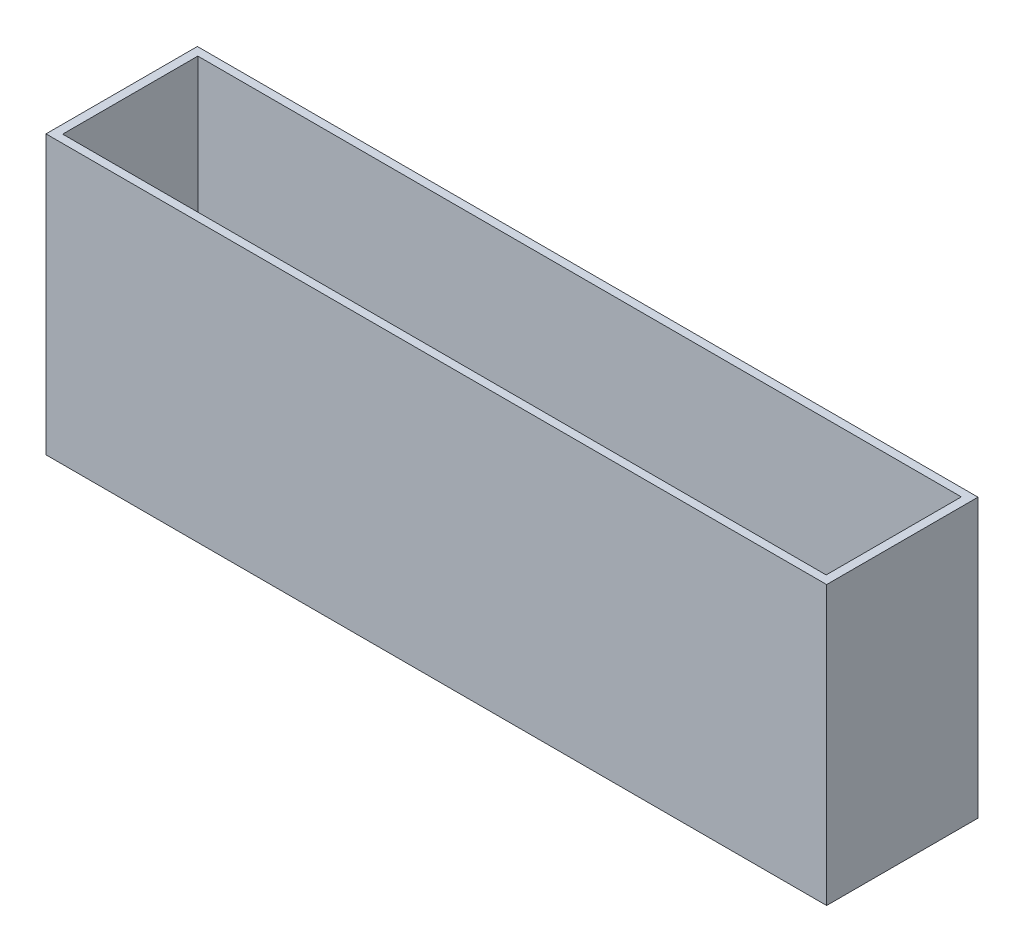
SolidWorks part; units mm, degrees
ref_plane "Front Plane" through (0, 0, 0) normal (0, 0, 1) x (1, 0, 0)
ref_plane "Top Plane" through (0, 0, 0) normal (0, 1, 0) x (1, 0, 0)
ref_plane "Right Plane" through (0, 0, 0) normal (1, 0, 0) x (0, 0, -1)
sketch "Sketch1" plane through (0, 0, 0) normal (0, 1, 0) x (1, 0, 0)
  line L1 (52.07, -10.0965) -> (-52.07, -10.0965)
  line L2 (52.07, -10.0965) -> (52.07, 10.0965)
  line L3 (52.07, 10.0965) -> (-52.07, 10.0965)
  line L4 (-52.07, -10.0965) -> (-52.07, 10.0965)
  line L5 (52.07, -10.0965) -> (-52.07, 10.0965) construction
  line L6 (52.07, 10.0965) -> (-52.07, -10.0965) construction
  point P0 (0, 0)
  dimension "D1" = 20.193
  dimension "D2" = 104.14
extrude "Boss-Extrude1" add sketch "Sketch1" along normal blind 5.08
sketch "Sketch2" plane through (0, 5.08, 0) normal (0, 1, 0) x (1, 0, 0)
  line L1 (52.07, -10.0965) -> (-52.07, -10.0965)
  line L2 (52.07, -10.0965) -> (52.07, 10.0965)
  line L3 (52.07, 10.0965) -> (-52.07, 10.0965)
  line L4 (-52.07, -10.0965) -> (-52.07, 10.0965)
  line L5 (52.07, -10.0965) -> (-52.07, 10.0965) construction
  line L6 (52.07, 10.0965) -> (-52.07, -10.0965) construction
  line L7 (50.927, -9.017) -> (-50.927, -9.017)
  line L8 (50.927, -9.017) -> (50.927, 9.017)
  line L9 (50.927, 9.017) -> (-50.927, 9.017)
  line L10 (-50.927, -9.017) -> (-50.927, 9.017)
  line L11 (50.927, -9.017) -> (-50.927, 9.017) construction
  line L12 (50.927, 9.017) -> (-50.927, -9.017) construction
  line L17 (52.07, -10.0965) -> (-52.07, -10.0965)
  line L18 (52.07, -10.0965) -> (52.07, 10.0965)
  line L19 (52.07, 10.0965) -> (-52.07, 10.0965)
  line L20 (-52.07, -10.0965) -> (-52.07, 10.0965)
  line L21 (52.07, -10.0965) -> (-52.07, 10.0965) construction
  line L22 (52.07, 10.0965) -> (-52.07, -10.0965) construction
  point P0 (0, 0)
  point P7 (0, 0)
  point P12 (0, 0)
  line M7 (-52.07, 10.0965) -> (-52.07, -10.0965)
  line M8 (-52.07, -10.0965) -> (52.07, -10.0965)
  line M9 (52.07, -10.0965) -> (52.07, 10.0965)
  line M10 (52.07, 10.0965) -> (-52.07, 10.0965)
  dimension "D1" = 101.854
  dimension "D2" = 18.034
extrude "Boss-Extrude2" add sketch "Sketch2" along normal blind 32.004 contours L7 L10 L9 L8 M10 M7 M8 M9
sketch "Sketch3" plane through (0, 5.08, 0) normal (0, 1, 0) x (1, 0, 0)
  line L0 (50.927, 0) -> (-50.927, 0) construction
  line L1 (-50.927, -9.017) -> (-50.927, 9.017) construction
  line L2 (-50.927, -9.017) -> (-50.927, 9.017) construction
  line L3 (-38.227, -8.763) -> (-5.207, -8.763)
  line L4 (-38.227, -8.763) -> (-38.227, 8.763)
  line L5 (-38.227, 8.763) -> (-5.207, 8.763)
  line L6 (-5.207, -8.763) -> (-5.207, 8.763)
  line L7 (-38.227, -8.763) -> (-5.207, 8.763) construction
  line L8 (-38.227, 8.763) -> (-5.207, -8.763) construction
  line L9 (28.321, -8.763) -> (45.847, -8.763)
  line L10 (28.321, -8.763) -> (28.321, 8.763)
  line L11 (28.321, 8.763) -> (45.847, 8.763)
  line L12 (45.847, -8.763) -> (45.847, 8.763)
  line L13 (28.321, -8.763) -> (45.847, 8.763) construction
  line L14 (28.321, 8.763) -> (45.847, -8.763) construction
  line L15 (50.927, -9.017) -> (50.927, 9.017) construction
  circle A0 centre (11.303, 0) radius 2.54
  point P0 (-21.717, 0)
  point P6 (0, 0)
  point P12 (37.084, 0)
  dimension "D4" = 5.08
  dimension "D8" = 62.23
  dimension "D1" = 33.02
  dimension "D2" = 17.526
  dimension "D3" = 12.7
  dimension "D5" = 17.526
  dimension "D6" = 17.526
  dimension "D7" = 5.08
extrude "Cut-Extrude1" cut sketch "Sketch3" against normal blind 32.004
